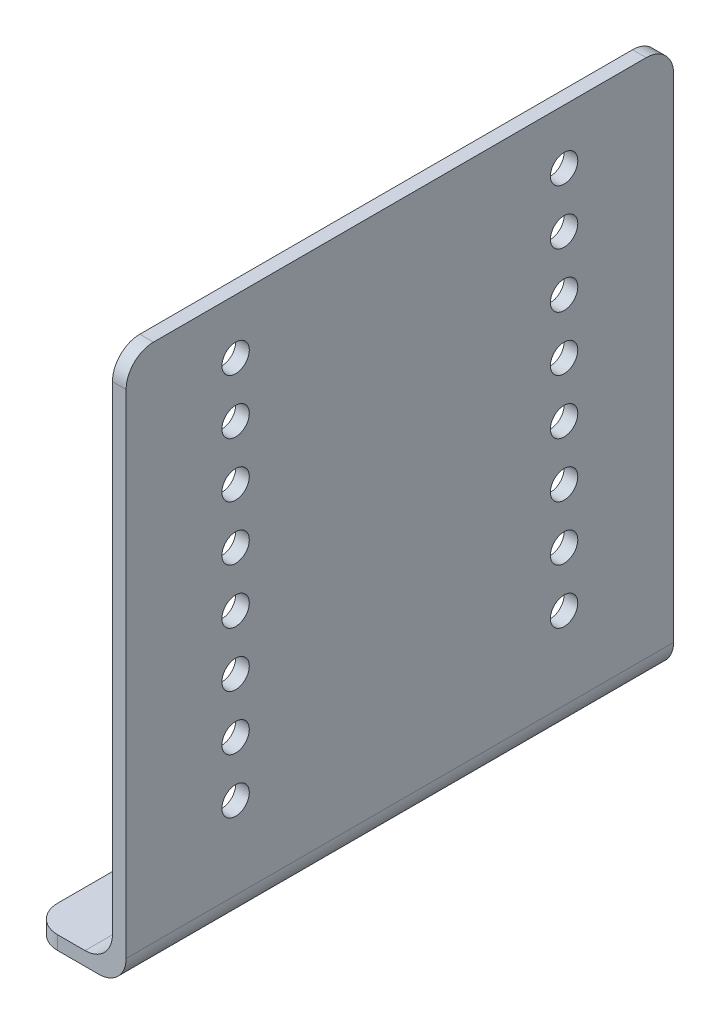
SolidWorks part; units mm, degrees
ref_plane "Front Plane" through (0, 0, 0) normal (0, 0, 1) x (1, 0, 0)
ref_plane "Top Plane" through (0, 0, 0) normal (0, 1, 0) x (1, 0, 0)
ref_plane "Right Plane" through (0, 0, 0) normal (1, 0, 0) x (0, 0, -1)
sketch "Sketch1" plane through (0, 0, 0) normal (1, 0, 0) x (0, 0, -1)
  line L1 (0, 0) -> (200, 0)
  line L2 (0, 0) -> (0, 190)
  line L3 (10, 200) -> (190, 200)
  line L4 (200, 0) -> (200, 190)
  circle A0 centre (40, 40) radius 5
  circle A1 centre (40, 60) radius 5
  circle A2 centre (40, 80) radius 5
  circle A3 centre (40, 100) radius 5
  circle A4 centre (40, 120) radius 5
  circle A5 centre (40, 140) radius 5
  circle A6 centre (40, 160) radius 5
  circle A7 centre (40, 180) radius 5
  circle A8 centre (160, 180) radius 5
  circle A9 centre (160, 40) radius 5
  circle A10 centre (160, 80) radius 5
  circle A11 centre (160, 60) radius 5
  circle A12 centre (160, 100) radius 5
  circle A13 centre (160, 120) radius 5
  circle A14 centre (160, 140) radius 5
  circle A15 centre (160, 160) radius 5
  arc A16 (190, 200) -> (200, 190) centre (190, 190) cw
  arc A17 (10, 200) -> (0, 190) centre (10, 190) ccw
  point P39 (200, 200)
  point P42 (0, 200)
  dimension "D3" = 10
  dimension "D7" = 2
  dimension "D8" = 10
  dimension "D1" = 200
  dimension "D2" = 200
  dimension "D4" = 40
  dimension "D5" = 40
  dimension "D6" = 8
extrude "Boss-Extrude1" add sketch "Sketch1" along normal blind 5
sketch "Sketch3" plane through (0, 0, 0) normal (-1, 0, 0) x (0, 0, 1)
  line L0 (2.75, 0) -> (-2.75, 0) construction
  line L1 (-199.4961, 0) -> (0, 0)
  line L2 (-199.4961, 0) -> (-199.4961, 5)
  line L3 (-199.4961, 5) -> (0, 5)
  line L4 (0, 0) -> (0, 5)
  line L5 (0, -2.75) -> (0, 2.75) construction
  dimension "D1" = 5
extrude "Boss-Extrude2" add sketch "Sketch3" along normal blind 30
fillet "Fillet1" radius 10 1 edges at (5, 0, -100)
sketch "Sketch7" plane through (0, 0, 0) normal (0, 0, 1) x (1, 0, 0)
  line L0 (0, 190) -> (0, 5) construction
  line L1 (-5, 0) -> (-30, 0) construction
  line L2 (0, 15) -> (0, 5)
  line L3 (0, 5) -> (-10, 5)
  arc A0 (-10, 5) -> (0, 15) centre (-10, 15) ccw
  dimension "D1" = 10
  dimension "D2" = 15
extrude "Boss-Extrude3" add sketch "Sketch7" against normal blind 200
fillet "Fillet2" radius 10 2 edges at (-30, 2.5, -199.4961) (-30, 2.5, 0)
sketch "Sketch8" plane through (0, 5, 0) normal (0, 1, 0) x (1, 0, 0)
  line L0 (-20, 199.4961) -> (-10, 199.4961) construction
  line L1 (-30, 10) -> (-30, 189.4961) construction
  circle A0 centre (-20, 169.4961) radius 5
  circle A1 centre (-20, 29.4961) radius 5
  dimension "D1" = 10
  dimension "D3" = 10
  dimension "D5" = 140
  dimension "D2" = 30
  dimension "D4" = 2
extrude "Cut-Extrude1" cut sketch "Sketch8" against normal blind 200
